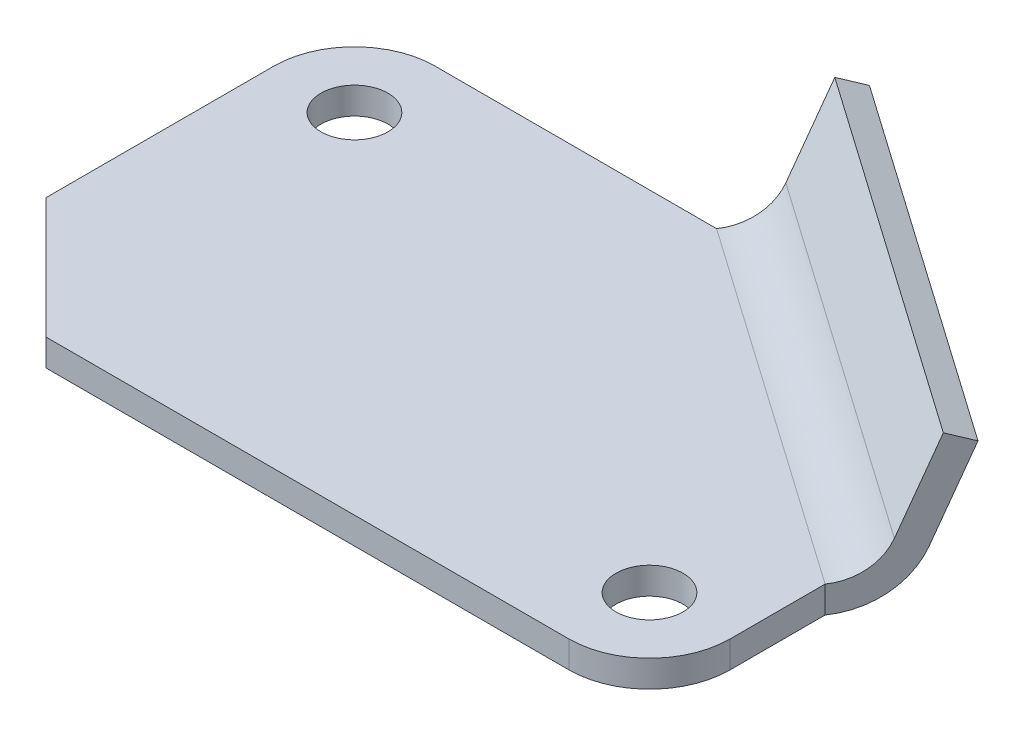
SolidWorks part; units mm, degrees
material "Manganese Bronze"
ref_plane "Front Plane" through (0, 0, 0) normal (0, 0, 1) x (1, 0, 0)
ref_plane "Top Plane" through (0, 0, 0) normal (0, 1, 0) x (1, 0, 0)
ref_plane "Right Plane" through (0, 0, 0) normal (1, 0, 0) x (0, 0, -1)
sketch "Sketch1" plane through (0, 0, 0) normal (0, 1, 0) x (1, 0, 0)
  line L0 (54, 64) -> (108, 26.1888)
  line L1 (18, 0) -> (96, 0)
  line L2 (0, 18) -> (0, 52)
  line L3 (12, 64) -> (108, 64)
  line L4 (108, 12) -> (108, 64)
  line L5 (0, 18) -> (18, 0)
  circle A0 centre (12, 52) radius 5
  circle A1 centre (96, 12) radius 5
  arc A2 (96, 0) -> (108, 12) centre (96, 12) ccw
  arc A3 (0, 52) -> (12, 64) centre (12, 52) cw
  point P0 (0, 0)
  point P13 (108, 0)
  point P16 (0, 64)
  dimension "D3" = 12
  dimension "D4" = 10
  dimension "D1" = 108
  dimension "D2" = 64
  dimension "D5" = 35
  dimension "D6" = 54
extrude "Boss-Extrude1" add sketch "Sketch1" along normal blind 4 contours A3 L2 L1 A2 L4 L0 L3 A1 A0
ref_plane "Plane2" through (60.1644, 0, 42.1276) normal (0.8192, 0, 0.5736) x (0, -1, 0)
sketch "Sketch4" plane through (60.1644, 0, 42.1276) normal (0.8192, 0, 0.5736) x (0, -1, 0)
  line L1 (-4, 83.3989) -> (0, 83.3989) construction
  line L2 (-4, 71.7761) -> (-4, 83.3989) construction
  line L3 (-9.0031, 90.8163) -> (-21.9837, 96.0608)
  line L4 (-21.9837, 96.0608) -> (-20.4853, 99.7696)
  line L5 (-20.4853, 99.7696) -> (-7.5047, 94.5251)
  line L7 (0, 71.7761) -> (0, 83.3989) construction
  line L8 (0, 83.3989) -> (-4, 83.3989)
  arc A0 (-4, 83.3989) -> (-9.0031, 90.8163) centre (-12, 83.3989) ccw
  arc A1 (-7.5047, 94.5251) -> (0, 83.3989) centre (-12, 83.3989) cw
  dimension "D3" = 12
  dimension "D1" = 112
  dimension "D2" = 14
extrude "Boss-Extrude4" add sketch "Sketch4" against normal up to vertex (65.9218 mm away)
